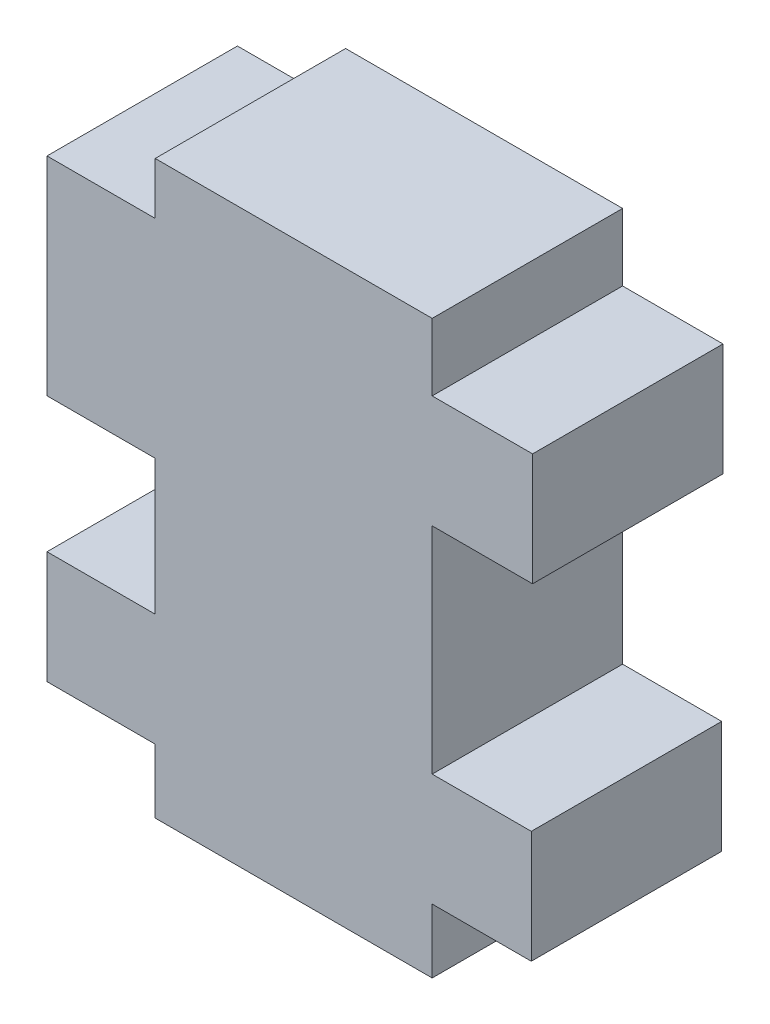
SolidWorks part; units mm, degrees
ref_plane "前视基准面" through (0, 0, 0) normal (0, 0, 1) x (1, 0, 0)
ref_plane "上视基准面" through (0, 0, 0) normal (0, 1, 0) x (1, 0, 0)
ref_plane "右视基准面" through (0, 0, 0) normal (1, 0, 0) x (0, 0, -1)
sketch "草图1" plane through (0, 0, 0) normal (0, 0, 1) x (1, 0, 0)
  line L0 (-1.425, 1.35) -> (-0.8, 1.35)
  line L1 (-0.8, 1.35) -> (-0.8, 1.65)
  line L2 (-0.8, 1.65) -> (0.8, 1.65)
  line L3 (0.8, 1.65) -> (0.8, 1.262)
  line L4 (0.8, 1.262) -> (1.38, 1.262)
  line L5 (1.38, 1.262) -> (1.38, 0.612)
  line L6 (1.38, 0.612) -> (0.8, 0.612)
  line L7 (0.8, 0.612) -> (0.8, -0.63)
  line L8 (0.8, -0.63) -> (1.3725, -0.63)
  line L9 (1.3725, -0.63) -> (1.3725, -1.28)
  line L10 (1.3725, -1.28) -> (0.8, -1.28)
  line L11 (0.8, -1.28) -> (0.8, -1.65)
  line L12 (0.8, -1.65) -> (-0.8, -1.65)
  line L13 (-0.8, -1.65) -> (-0.8, -1.28)
  line L14 (-0.8, -1.28) -> (-1.425, -1.28)
  line L15 (-1.425, -1.28) -> (-1.425, -0.63)
  line L16 (-1.425, -0.63) -> (-0.8, -0.63)
  line L17 (-0.8, -0.63) -> (-0.8, 0.15)
  line L18 (-0.8, 0.15) -> (-1.425, 0.15)
  line L19 (-1.425, 0.15) -> (-1.425, 1.35)
extrude "Component_Outline" add sketch "草图1" along normal blind 1.1 separate body
sketch3d "3D草图1"
  line L0 (0, 0, 0) -> (1, 0, 0)
  line L1 (0, 0, 0) -> (0, 1, 0)
  line L2 (0, 0, 0) -> (0, 0, 1)
  point P0 (0, 0, 0)
